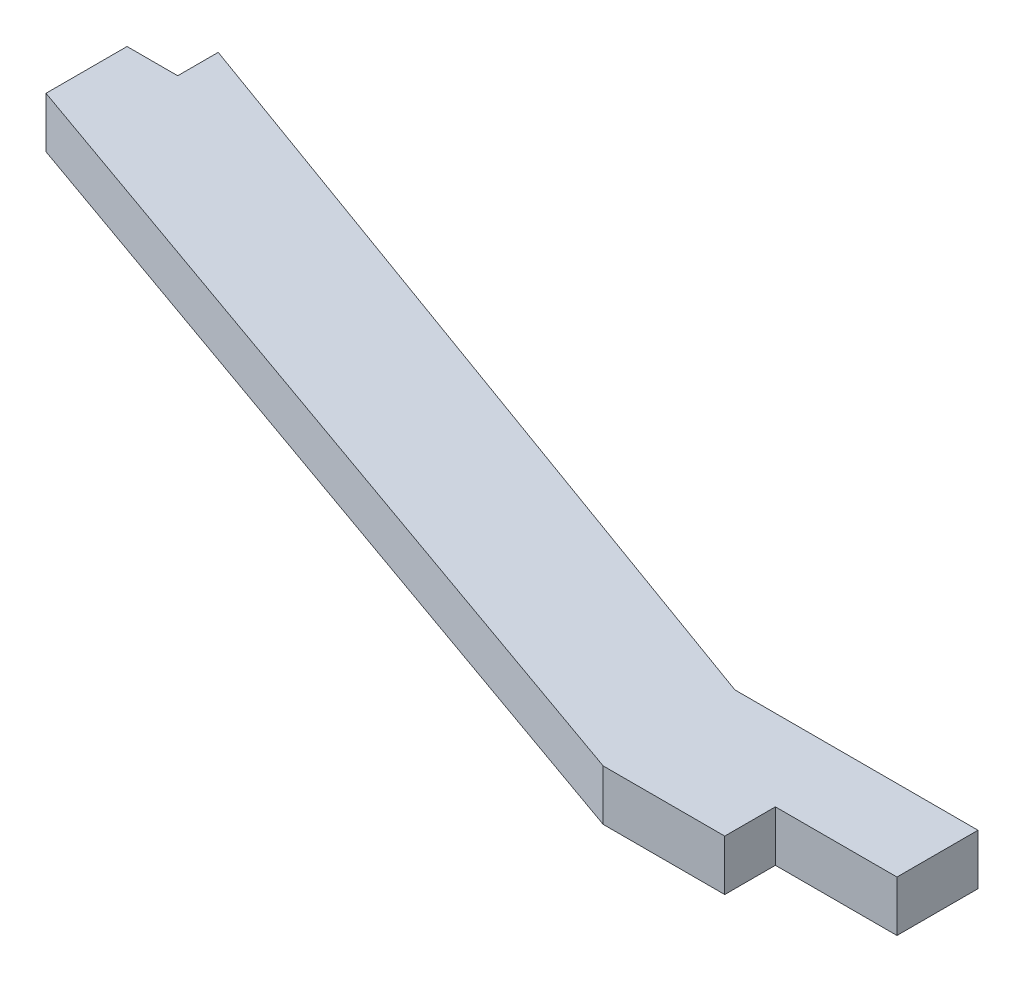
SolidWorks part; units mm, degrees
material "Balsa"
ref_plane "Front Plane" through (0, 0, 0) normal (0, 0, 1) x (1, 0, 0)
ref_plane "Top Plane" through (0, 0, 0) normal (0, 1, 0) x (1, 0, 0)
ref_plane "Right Plane" through (0, 0, 0) normal (1, 0, 0) x (0, 0, -1)
sketch "Sketch2" plane through (0, 0, 0) normal (0, 1, 0) x (1, 0, 0)
  line L0 (0, 0) -> (0, -5.08)
  line L1 (0, -5.08) -> (53.975, -24.13)
  line L2 (53.975, -24.13) -> (61.595, -24.13)
  line L3 (61.595, -24.13) -> (61.595, -20.955)
  line L4 (61.595, -20.955) -> (69.215, -20.955)
  line L5 (69.215, -20.955) -> (69.215, -15.875)
  line L6 (69.215, -15.875) -> (53.975, -15.875)
  line L7 (53.975, -15.875) -> (3.175, 2.54)
  line L8 (3.175, 2.54) -> (3.175, 0)
  line L9 (3.175, 0) -> (0, 0)
  dimension "D1" = 5.08
  dimension "D2" = 3.175
  dimension "D3" = 19.05
  dimension "2.425" = 53.975
  dimension "D5" = 7.62
  dimension "0.1" = 2.54
  dimension "D6" = 7.62
  dimension "D7" = 5.08
  dimension "D8" = 3.175
extrude "Boss-Extrude1" add sketch "Sketch2" along normal blind 3.175
